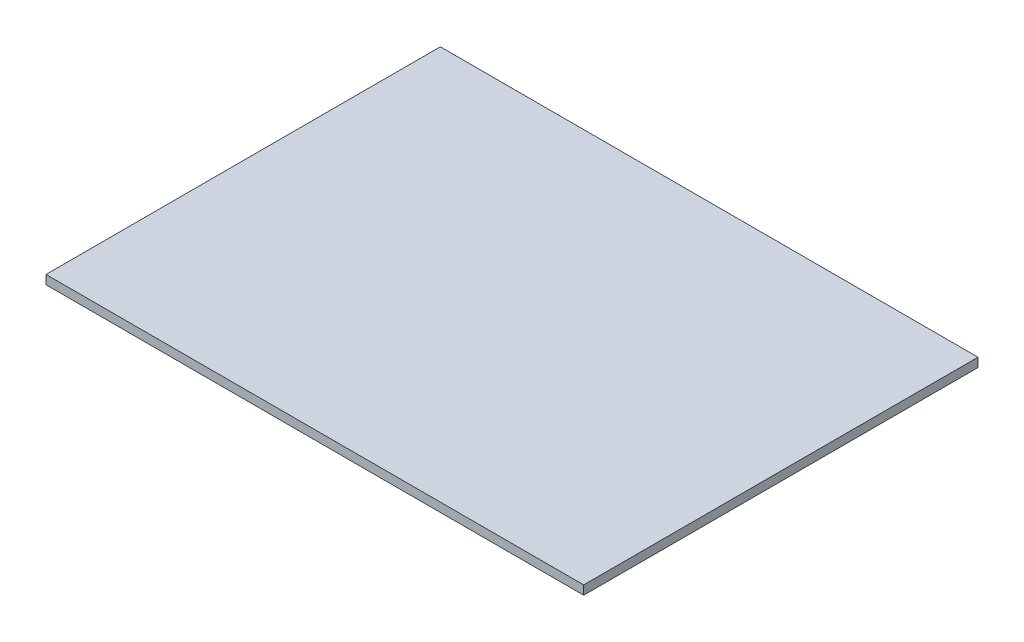
SolidWorks part; units mm, degrees
material "Maple"
ref_plane "Front Plane" through (0, 0, 0) normal (0, 0, 1) x (1, 0, 0)
ref_plane "Top Plane" through (0, 0, 0) normal (0, 1, 0) x (1, 0, 0)
ref_plane "Right Plane" through (0, 0, 0) normal (1, 0, 0) x (0, 0, -1)
sketch "Sketch1" plane through (0, 0, 0) normal (0, 1, 0) x (1, 0, 0)
  line L1 (-150, 110) -> (150, 110)
  line L2 (-150, 110) -> (-150, -110)
  line L3 (-150, -110) -> (150, -110)
  line L4 (150, 110) -> (150, -110)
  line L5 (-150, 110) -> (150, -110) construction
  line L6 (-150, -110) -> (150, 110) construction
  point P0 (0, 0)
  dimension "D1" = 300
  dimension "D2" = 220
extrude "Boss-Extrude1" add sketch "Sketch1" along normal blind 5
